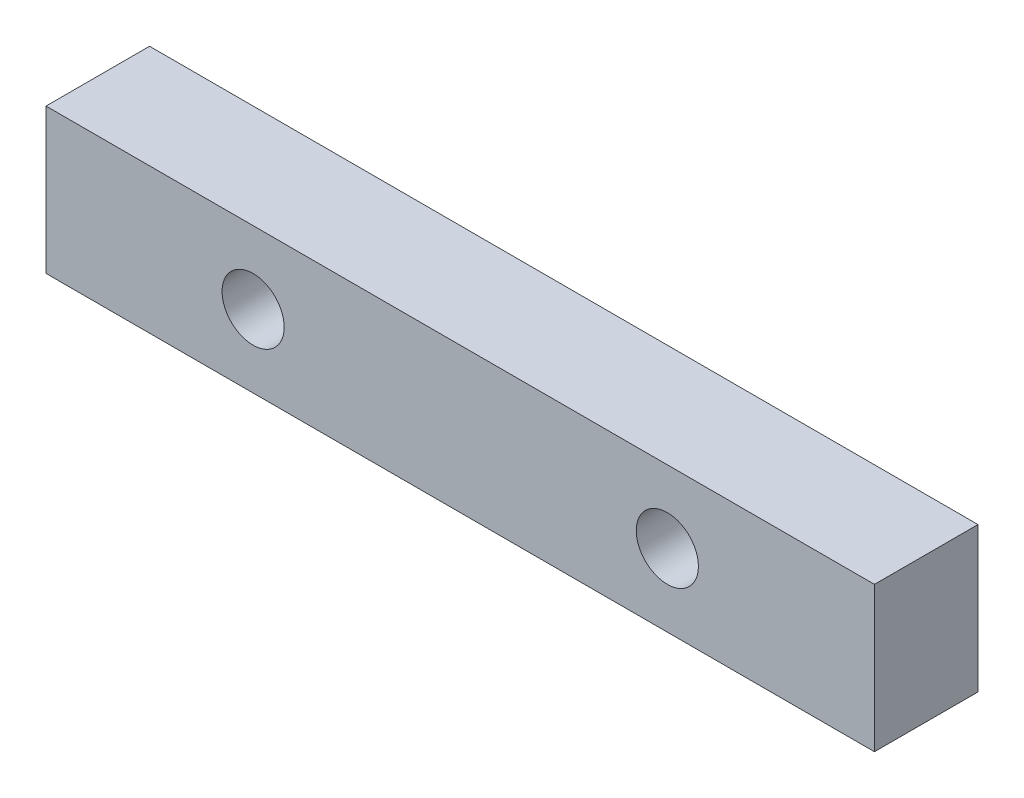
SolidWorks part; units mm, degrees
ref_plane "Ebene vorne" through (0, 0, 0) normal (0, 0, 1) x (1, 0, 0)
ref_plane "Ebene oben" through (0, 0, 0) normal (0, 1, 0) x (1, 0, 0)
ref_plane "Ebene rechts" through (0, 0, 0) normal (1, 0, 0) x (0, 0, -1)
sketch "Skizze1" plane through (0, 0, 0) normal (0, 0, 1) x (1, 0, 0)
  line L1 (-20, -3.5) -> (20, -3.5)
  line L2 (-20, -3.5) -> (-20, 3.5)
  line L3 (-20, 3.5) -> (20, 3.5)
  line L4 (20, -3.5) -> (20, 3.5)
  line L5 (-20, -3.5) -> (20, 3.5) construction
  line L6 (-20, 3.5) -> (20, -3.5) construction
  circle A0 centre (-10, 0) radius 1.5
  circle A1 centre (10, 0) radius 1.5
  point P0 (0, 0)
  dimension "D3" = 3
  dimension "D4" = 3
  dimension "D1" = 40
  dimension "D2" = 7
  dimension "D5" = 10
  dimension "D6" = 10
extrude "Aufsatz-Linear austragen1" add sketch "Skizze1" along normal blind 5
